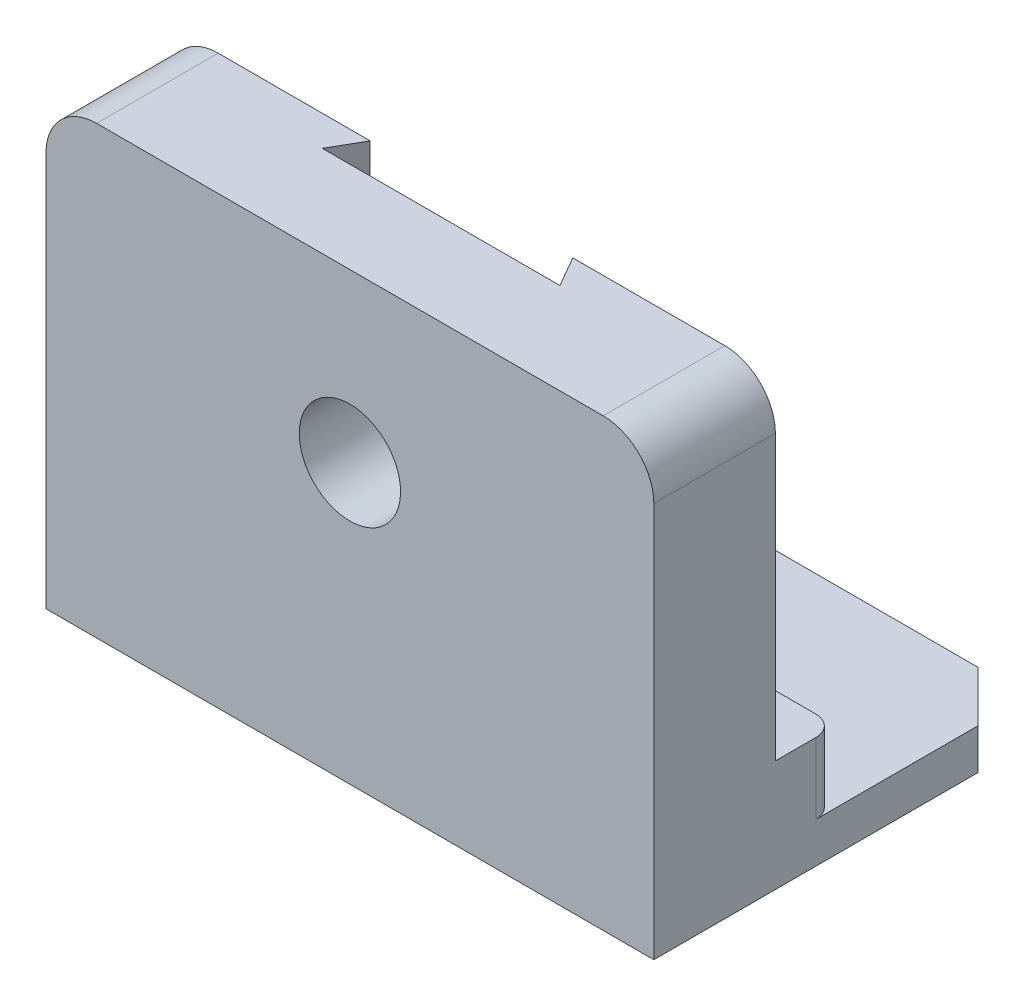
SolidWorks part; units mm, degrees
ref_plane "Piano frontale" through (0, 0, 0) normal (0, 0, 1) x (1, 0, 0)
ref_plane "Piano superiore" through (0, 0, 0) normal (0, 1, 0) x (1, 0, 0)
ref_plane "Piano destro" through (0, 0, 0) normal (1, 0, 0) x (0, 0, -1)
sketch "Schizzo2" plane through (0, 0, 0) normal (1, 0, 0) x (0, 0, -1)
  line L0 (0, 44) -> (12, 44)
  line L1 (12, 44) -> (12, 11)
  line L2 (12, 11) -> (37, 11)
  line L3 (37, 11) -> (37, 0)
  line L4 (37, 0) -> (0, 0)
  line L5 (0, 0) -> (0, 44)
  dimension "D1" = 44
  dimension "D2" = 33
  dimension "D3" = 37
  dimension "D4" = 25
extrude "Estrusione-Estrusione1" add sketch "Schizzo2" along normal mid plane 60
sketch "Schizzo6" plane through (0, 11, 0) normal (0, 1, 0) x (1, 0, 0)
  line L0 (0, 0) -> (0, 37) construction
  line L1 (30, 37) -> (-30, 37) construction
  line L2 (-30, 37) -> (-4, 37)
  line L3 (-4, 37) -> (-4, 18)
  line L4 (-4, 18) -> (-30, 18)
  line L5 (-30, 37) -> (-30, 12) construction
  line L6 (-30, 18) -> (-30, 37)
  line L7 (4, 37) -> (4, 18)
  line L8 (4, 18) -> (30, 18)
  line L9 (30, 18) -> (30, 37)
  line L10 (30, 37) -> (4, 37)
  dimension "D1" = 26
  dimension "D2" = 19
extrude "Taglio-Estrusione2" cut sketch "Schizzo6" against normal blind 7
sketch "Schizzo7" plane through (0, 0, -12) normal (0, 0, -1) x (-1, 0, 0)
  line L0 (0, 44) -> (0, 13.4976) construction
  line L1 (-30, 44) -> (30, 44) construction
  line L2 (0, 44) -> (0, 27.5) construction
  line L3 (10, 44) -> (10, 27.5)
  line L4 (-10, 44) -> (-10, 27.5)
  line L5 (-10, 44) -> (10, 44)
  line L6 (-30, 0) -> (30, 0) construction
  arc A1 (-10, 27.5) -> (10, 27.5) centre (0, 27.5) ccw
  point P7 (0, 35.75)
  dimension "D2" = 27.5
  dimension "D1" = 20
extrude "Taglio-Estrusione3" cut sketch "Schizzo7" against normal blind 3 draft 30 contours A1 L3 L5 L4 draft outward yes
hole_wizard "Foro Ø10.0 (10)-1" positions "Schizzo9" profile "Schizzo10" hole size "Ø10.0" standard "ISO" end condition up to next
sketch "Schizzo9" plane through (0, 0, -9) normal (0, 0, -1) x (-1, 0, 0)
  line L0 (0, 0) -> (0, 44) construction
  line L1 (11.732, 44) -> (-11.7321, 44) construction
  line L3 (-30, 27.5) -> (30, 27.5) construction
  line L4 (-30, 11) -> (-30, 44) construction
  line L5 (30, 11) -> (30, 44) construction
  line L7 (-30, 0) -> (30, 0) construction
  point P18 (0, 27.5)
  point P21 (0, 0)
  dimension "D1" = 27.5
sketch "Schizzo10" plane through (0, 27.5, -9) normal (1, 0, 0) x (0, 1, 0)
  line L0 (0, 0) -> (0, 9)
  line L1 (0, 9) -> (5, 9)
  line L2 (5, 9) -> (5, 0)
  line L5 (5, 0) -> (0, 0)
  line L11 (0, -6.35) -> (0, 107.95) construction
  dimension "Thru Hole Dia." = 10
  dimension "Thru Hole Depth" = 9
hole_wizard "Foro Ø4.0 (4)-1" positions "Schizzo11" profile "Schizzo12" hole size "Ø4.0" standard "ISO" end condition up to next
sketch "Schizzo11" plane through (0, 11, 0) normal (0, 1, 0) x (1, 0, 0)
  line L0 (0, 37) -> (0, 0) construction
  line L1 (4, 37) -> (-4, 37) construction
  line L3 (-30, 15) -> (30, 15) construction
  line L4 (-30, 18) -> (-30, 12) construction
  line L5 (30, 18) -> (30, 12) construction
  line L7 (-24, 18) -> (-24, 12) construction
  line L8 (-30, 18) -> (-4, 18) construction
  line L9 (-10, 12) -> (-30, 12) construction
  line L11 (-4, 37) -> (-30, 37) construction
  point P26 (-24, 15)
  point P29 (24, 15)
  point P31 (0, 31)
  dimension "D1" = 24
  dimension "D2" = 22
  dimension "D3" = 6
sketch "Schizzo12" plane through (0, 11, -31) normal (1, 0, 0) x (0, 0, 1)
  line L0 (0, 0) -> (0, 11)
  line L1 (0, 11) -> (2, 11)
  line L2 (2, 11) -> (2, 0)
  line L5 (2, 0) -> (0, 0)
  line L11 (0, -6.35) -> (0, 107.95) construction
  dimension "Thru Hole Dia." = 4
  dimension "Thru Hole Depth" = 11
fillet "Raccordo1" radius 5 2 edges at (-30, 44, -6) (30, 44, -6)
fillet "Raccordo2" radius 6 2 edges at (4, 7.5, -18) (-4, 7.5, -18)
fillet "Raccordo3" radius 2 4 edges at (30, 7.5, -18) (4, 7.5, -37) (-4, 7.5, -37) (-30, 7.5, -18)
chamfer "Smusso1" distance 5 angle 45 2 edges at (-30, 2, -37) (30, 2, -37)
